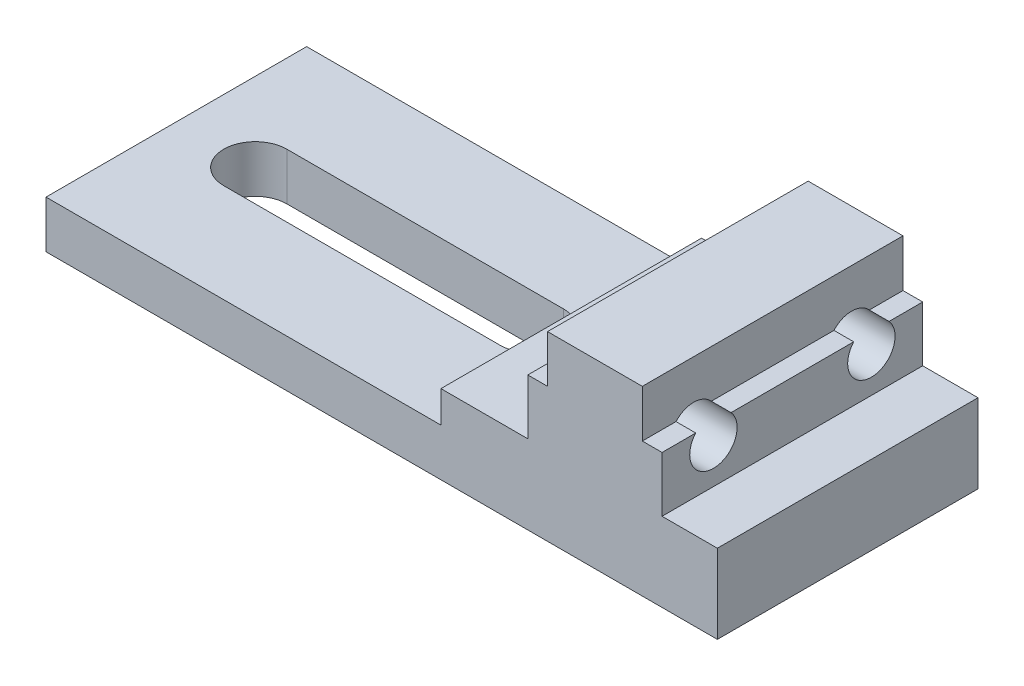
SolidWorks part; units mm, degrees
ref_plane "前基準面" through (0, 0, 0) normal (0, 0, 1) x (1, 0, 0)
ref_plane "上基準面" through (0, 0, 0) normal (0, 1, 0) x (1, 0, 0)
ref_plane "右基準面" through (0, 0, 0) normal (1, 0, 0) x (0, 0, -1)
sketch "草圖1" plane through (0, 0, 0) normal (0, 0, 1) x (1, 0, 0)
  line L0 (0, 0) -> (85, 0)
  line L1 (85, 0) -> (85, 10)
  line L2 (85, 10) -> (78, 10)
  line L3 (78, 10) -> (78, 17)
  line L4 (78, 17) -> (75.5, 17)
  line L5 (75.5, 17) -> (75.5, 23)
  line L6 (75.5, 23) -> (63.5, 23)
  line L7 (63.5, 23) -> (63.5, 17)
  line L8 (63.5, 17) -> (61, 17)
  line L9 (61, 17) -> (61, 10)
  line L10 (50, 6) -> (0, 6)
  line L11 (0, 6) -> (0, 0)
  line L12 (50, 6) -> (50, 10)
  line L13 (50, 10) -> (61, 10)
  dimension "D1" = 85
  dimension "D2" = 6
  dimension "D3" = 10
  dimension "D4" = 12
  dimension "D5" = 17
  dimension "D6" = 2.5
  dimension "D7" = 13
  dimension "D8" = 7
  dimension "D9" = 7
  dimension "D10" = 50
  dimension "D11" = 10
extrude "填料-伸長1" add sketch "草圖1" along normal mid plane 33
sketch "草圖2" plane through (0, 6, 0) normal (0, 1, 0) x (1, 0, 0)
  line L0 (10, 0) -> (45, 0) construction
  line L1 (10, 4) -> (45, 4)
  line L2 (10, -4) -> (45, -4)
  arc A0 (10, 4) -> (10, -4) centre (10, 0) ccw
  arc A1 (45, -4) -> (45, 4) centre (45, 0) ccw
  point P3 (27.5, 0)
  dimension "D1" = 8
  dimension "D2" = 35
  dimension "D3" = 10
extrude "除料-伸長1" cut sketch "草圖2" against normal through all
sketch "草圖3" plane through (78, 0, 0) normal (1, 0, 0) x (0, 0, -1)
  line L0 (0, 0) -> (0, 24.1338) construction
  line L1 (-16.5, 0) -> (16.5, 0) construction
  line L2 (-16.5, 23) -> (16.5, 23) construction
  circle A0 centre (-10, 15) radius 3
  circle A1 centre (10, 15) radius 3
  dimension "D1" = 20
  dimension "D2" = 6
  dimension "D3" = 8
extrude "除料-伸長2" cut sketch "草圖3" against normal blind 33
